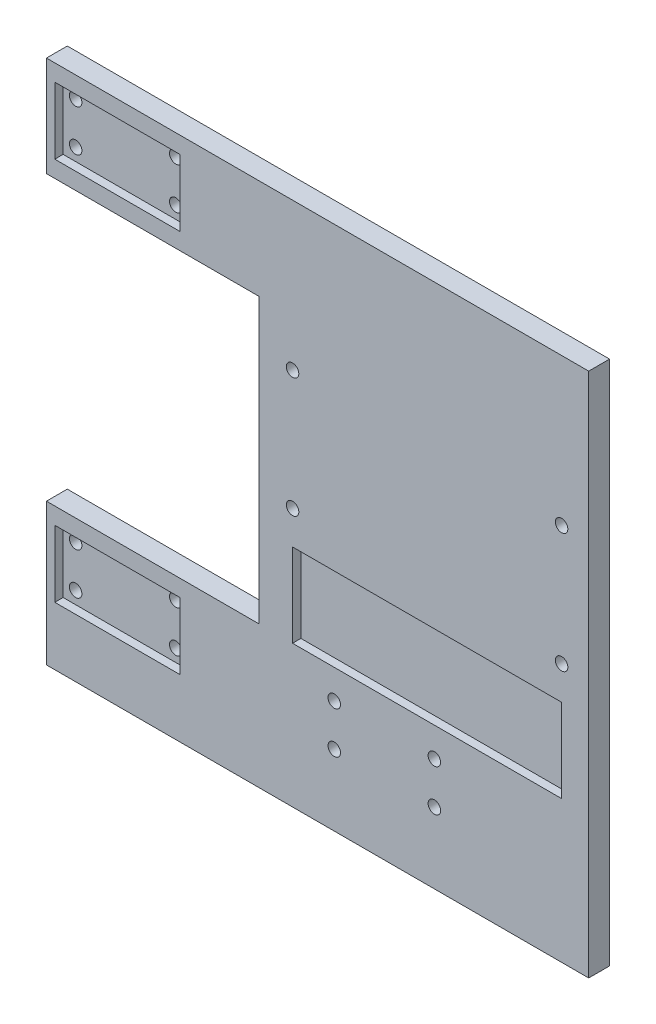
SolidWorks part; units mm, degrees
ref_plane "前视基准面" through (0, 0, 0) normal (0, 0, 1) x (1, 0, 0)
ref_plane "上视基准面" through (0, 0, 0) normal (0, 1, 0) x (1, 0, 0)
ref_plane "右视基准面" through (0, 0, 0) normal (1, 0, 0) x (0, 0, -1)
other "Configuration Table"
sketch "草图1" plane through (0, 0, 0) normal (0, 0, 1) x (1, 0, 0)
  line L0 (0, 0) -> (0, 30)
  line L1 (0, 30) -> (120, 30)
  line L2 (120, 30) -> (120, -96)
  line L3 (120, -96) -> (0, -96)
  line L4 (0, -96) -> (0, -56)
  line L5 (0, -56) -> (45, -56)
  line L6 (45, -56) -> (45, 0)
  line L7 (45, 0) -> (0, 0)
  dimension "D1" = 30
  dimension "D2" = 56
  dimension "D3" = 40
  dimension "D4" = 45
  dimension "D5" = 120
  dimension "D6" = 120
extrude "凸台-拉伸2" add sketch "草图1" along normal blind 5
sketch "草图3" plane through (0, 0, 5) normal (0, 0, 1) x (1, 0, 0)
  line L0 (0, 0) -> (0, 10)
  line L1 (0, 30) -> (0, 0) construction
  line L2 (0, 10) -> (17, 10)
  line L3 (-955, -28) -> (49045, -28) construction
  line L4 (2, 1.95) -> (32, 1.95)
  line L5 (2, 1.95) -> (2, 18.05)
  line L6 (2, 18.05) -> (32, 18.05)
  line L7 (32, 1.95) -> (32, 18.05)
  line L8 (2, 1.95) -> (32, 18.05) construction
  line L9 (2, 18.05) -> (32, 1.95) construction
  line L10 (45, 0) -> (45, -56) construction
  line L11 (2, -74.05) -> (32, -57.95) construction
  line L12 (2, -57.95) -> (32, -74.05) construction
  line L13 (32, -57.95) -> (32, -74.05)
  line L14 (2, -74.05) -> (32, -74.05)
  line L15 (2, -57.95) -> (2, -74.05)
  line L16 (2, -57.95) -> (32, -57.95)
  line L17 (0, -66) -> (17, -66)
  line L18 (0, -56) -> (0, -66)
  point P15 (45, -28)
  dimension "D1" = 10
  dimension "D2" = 17
  dimension "D3" = 16.1
  dimension "D4" = 30
extrude "切除-拉伸1" cut sketch "草图3" against normal blind 2
sketch "草图4" plane through (0, 0, 3) normal (0, 0, 1) x (1, 0, 0)
  line L0 (2, 18.05) -> (17, 18.05)
  line L5 (2, 18.05) -> (32, 18.05) construction
  line L6 (17, 18.05) -> (17, 10)
  line L7 (-998, 10) -> (49002, 10) construction
  line L8 (2, 2) -> (32, 2)
  line L9 (2, 2) -> (2, 18)
  line L10 (2, 18) -> (32, 18)
  line L11 (32, 2) -> (32, 18)
  line L12 (2, 2) -> (32, 18) construction
  line L13 (2, 18) -> (32, 2) construction
  line L14 (2, 18) -> (5, 18)
  line L15 (2, 18) -> (2, 15)
  line L16 (2, 15) -> (5, 15)
  line L17 (5, 18) -> (5, 15)
  line L18 (-955, -28) -> (49045, -28) construction
  line L19 (45, 0) -> (45, -56) construction
  circle A0 centre (5, 15) radius 1.55
  circle A1 centre (29, 15) radius 1.55
  circle A2 centre (29, 5) radius 1.55
  circle A3 centre (5, 5) radius 1.55
  circle A4 centre (5, -61) radius 1.55
  circle A5 centre (29, -61) radius 1.55
  circle A6 centre (29, -71) radius 1.55
  circle A7 centre (5, -71) radius 1.55
  point P20 (2, 10)
  point P29 (45, -28)
  dimension "D5" = 3.1
  dimension "D1" = 30
  dimension "D2" = 16
  dimension "D3" = 3
  dimension "D4" = 3
extrude "切除-拉伸2" cut sketch "草图4" against normal up to next contours A1 | A2 | L16 A0 L17 | L17 A0 L16 | A3 | A4 | A7 | A5 | A6
sketch "草图5" plane through (0, 0, 5) normal (0, 0, 1) x (1, 0, 0)
  line L0 (17, -74.05) -> (17, 18.05) construction
  line L1 (2, -74.05) -> (32, -74.05) construction
  line L2 (2, 18.05) -> (32, 18.05) construction
  line L3 (17, -74.05) -> (17, -85.05) construction
  line L4 (17, -85.05) -> (17, -96) construction
  line L5 (0, -96) -> (120, -96) construction
  line L6 (17, -96) -> (77, -96)
  line L7 (45, -56) -> (0, -56) construction
  line L8 (17, -56) -> (49, -56)
  line L9 (17, -56) -> (17, 0)
  line L10 (17, 0) -> (49, 0)
  line L11 (49, -56) -> (49, 0)
  dimension "D1" = 11
  dimension "D2" = 60
  dimension "D3" = 32
extrude "切除-拉伸3" cut sketch "草图5" against normal up to next contours L8 L11 L10 L9
sketch "草图7" plane through (0, 0, 5) normal (0, 0, 1) x (1, 0, 0)
  line L0 (49, -56) -> (59, -56)
  line L2 (59, -56) -> (99.5, -56)
  line L3 (59, -56) -> (59, -15.5)
  line L4 (59, -15.5) -> (99.5, -15.5)
  line L5 (99.5, -56) -> (99.5, -15.5)
  dimension "D1" = 10
  dimension "D2" = 40.5
  dimension "D3" = 40.5
extrude "凸台-拉伸4" add sketch "草图7" along normal blind 2 contours L2 L5 L4 L3
sketch "草图8" plane through (0, 0, 5) normal (0, 0, 1) x (1, 0, 0)
  line L0 (17, -998.05) -> (17, 49001.95) construction
  line L1 (2, 1.95) -> (32, 1.95) construction
  line L2 (59, -56) -> (69.5, -56)
  line L3 (59, -56) -> (99.5, -56) construction
  line L4 (69.5, -1056) -> (69.5, 48944) construction
  line L5 (69.5, -56) -> (69.5, -60.5)
  line L6 (69.5, -60.5) -> (69.5, -70.5)
  line L8 (54.25, -78.75) -> (84.75, -78.75)
  line L9 (54.25, -78.75) -> (54.25, -62.25)
  line L10 (54.25, -62.25) -> (84.75, -62.25)
  line L11 (84.75, -78.75) -> (84.75, -62.25)
  line L12 (54.25, -78.75) -> (84.75, -62.25) construction
  line L13 (54.25, -62.25) -> (84.75, -78.75) construction
  point P5 (17, 1.95)
  dimension "D1" = 10.5
  dimension "D2" = 4.5
  dimension "D3" = 10
  dimension "D4" = 30.5
  dimension "D5" = 16.5
extrude "切除-拉伸4" cut sketch "草图8" against normal blind 2
sketch "草图9" plane through (0, 0, 3) normal (0, 0, 1) x (1, 0, 0)
  line L0 (-945.75, -70.5) -> (49054.25, -70.5) construction
  line L1 (54.25, -62.25) -> (57.5, -62.25)
  line L2 (54.25, -62.25) -> (54.25, -65.5)
  line L3 (54.25, -65.5) -> (57.5, -65.5)
  line L4 (57.5, -62.25) -> (57.5, -65.5)
  line L5 (54.25, -78.75) -> (54.25, -62.25) construction
  line L6 (69.5, -1062.25) -> (69.5, 48937.75) construction
  line L7 (54.25, -62.25) -> (84.75, -62.25) construction
  circle A0 centre (57.5, -65.5) radius 1.55
  circle A1 centre (81.5, -65.5) radius 1.55
  circle A2 centre (81.5, -75.5) radius 1.55
  circle A3 centre (57.5, -75.5) radius 1.55
  point P11 (54.25, -70.5)
  point P16 (69.5, -62.25)
  dimension "D3" = 3.1
  dimension "D1" = 3.25
  dimension "D2" = 3.25
extrude "切除-拉伸6" cut sketch "草图9" against normal through all contours A1 | A0 | A3 | A2
sketch "草图10" plane through (0, 0, 7) normal (0, 0, 1) x (1, 0, 0)
  line L1 (59, -56) -> (119, -56)
  line L2 (59, -56) -> (59, -11)
  line L3 (59, -11) -> (119, -11)
  line L4 (119, -56) -> (119, -11)
  dimension "D1" = 60
  dimension "D2" = 45
extrude "凸台-拉伸5" add sketch "草图10" against normal blind 2
sketch "草图11" plane through (0, 0, 5) normal (0, 0, 1) x (1, 0, 0)
  line L1 (59, -11) -> (119, -11)
  line L2 (59, -11) -> (59, -56)
  line L3 (59, -56) -> (119, -56)
  line L4 (119, -11) -> (119, -56)
extrude "切除-拉伸8" cut sketch "草图11" along normal blind 2
sketch "草图12" plane through (0, 0, 5) normal (0, 0, 1) x (1, 0, 0)
  line L1 (2, 1.95) -> (32, 1.95)
  line L2 (2, 1.95) -> (2, 18.05)
  line L3 (2, 18.05) -> (32, 18.05)
  line L4 (32, 1.95) -> (32, 18.05)
  line L5 (2, -57.95) -> (32, -57.95)
  line L6 (2, -57.95) -> (2, -74.05)
  line L7 (2, -74.05) -> (32, -74.05)
  line L8 (32, -57.95) -> (32, -74.05)
  line L9 (54.25, -62.25) -> (84.75, -62.25)
  line L10 (54.25, -62.25) -> (54.25, -78.75)
  line L11 (54.25, -78.75) -> (84.75, -78.75)
  line L12 (84.75, -62.25) -> (84.75, -78.75)
extrude "凸台-拉伸6" add sketch "草图12" against normal blind 5
sketch "草图13" plane through (0, 0, 5) normal (0, 0, 1) x (1, 0, 0)
  line L0 (0, 0) -> (0, 10)
  line L1 (0, 30) -> (0, 0) construction
  line L2 (0, 10) -> (2, 10)
  line L3 (-951, -28) -> (49049, -28) construction
  line L4 (2, 10) -> (32, 10)
  line L5 (2, 10) -> (2, 26)
  line L6 (2, 26) -> (32, 26)
  line L7 (32, 10) -> (32, 26)
  line L8 (49, -56) -> (49, 0) construction
  line L9 (32, -66) -> (32, -82)
  line L10 (2, -82) -> (32, -82)
  line L11 (2, -66) -> (2, -82)
  line L12 (2, -66) -> (32, -66)
  line L13 (-998, 18) -> (49002, 18) construction
  line L14 (2, 26) -> (5, 26)
  line L15 (2, 26) -> (2, 23)
  line L16 (2, 23) -> (5, 23)
  line L17 (5, 26) -> (5, 23)
  line L19 (17, -974) -> (17, 49026) construction
  circle A0 centre (5, 23) radius 1.5
  circle A1 centre (29, 23) radius 1.5
  circle A2 centre (29, 13) radius 1.5
  circle A3 centre (5, 13) radius 1.5
  circle A4 centre (5, -69) radius 1.5
  circle A5 centre (29, -69) radius 1.5
  circle A6 centre (29, -79) radius 1.5
  circle A7 centre (5, -79) radius 1.5
  point P14 (49, -28)
  point P25 (2, 18)
  point P30 (17, 26)
  dimension "D7" = 3
  dimension "D1" = 10
  dimension "D2" = 2
  dimension "D3" = 16
  dimension "D4" = 30
  dimension "D5" = 3
  dimension "D6" = 3
extrude "切除-拉伸10" cut sketch "草图13" against normal blind 5 contours A4 | A7 | A2 | A1 | A3 | A6 | A5 | A0
sketch "草图14" plane through (0, 0, 5) normal (0, 0, 1) x (1, 0, 0)
  line L1 (2, 26) -> (32, 26)
  line L2 (2, 26) -> (2, 10)
  line L3 (2, 10) -> (32, 10)
  line L4 (32, 26) -> (32, 10)
  line L5 (2, -66) -> (32, -66)
  line L6 (2, -66) -> (2, -82)
  line L7 (2, -82) -> (32, -82)
  line L8 (32, -66) -> (32, -82)
extrude "切除-拉伸11" cut sketch "草图14" against normal blind 2
sketch "草图15" plane through (0, 0, 5) normal (0, 0, 1) x (1, 0, 0)
  line L0 (-2, 2) -> (-2, -58)
  line L1 (0, 0) -> (49, 0)
  line L2 (0, 0) -> (0, -56)
  line L3 (0, -56) -> (49, -56)
  line L4 (49, 0) -> (49, -56)
  line L5 (-2, -58) -> (51, -58)
  line L6 (51, 2) -> (51, -58)
  line L7 (-2, 2) -> (51, 2)
  dimension "D1" = 2
extrude "切除-拉伸12" cut sketch "草图15" against normal blind 5
sketch "草图16" plane through (0, 0, 5) normal (0, 0, 1) x (1, 0, 0)
  line L0 (51, -58) -> (61, -58)
  line L1 (61, -58) -> (61, -66)
  line L3 (61, -66) -> (91, -66)
  line L4 (61, -66) -> (61, -82)
  line L5 (61, -82) -> (91, -82)
  line L6 (91, -66) -> (91, -82)
  dimension "D1" = 10
  dimension "D2" = 30
  dimension "D3" = 16
extrude "切除-拉伸13" cut sketch "草图16" against normal blind 2 contours L6 L3 L4 L5
sketch "草图17" plane through (0, 0, 3) normal (0, 0, 1) x (1, 0, 0)
  line L0 (-939, -74) -> (49061, -74) construction
  line L1 (61, -66) -> (64, -66)
  line L2 (61, -66) -> (61, -69)
  line L3 (61, -69) -> (64, -69)
  line L4 (64, -66) -> (64, -69)
  line L5 (61, -66) -> (61, -82) construction
  line L6 (76, -1066) -> (76, 48934) construction
  line L7 (61, -66) -> (91, -66) construction
  circle A0 centre (64, -69) radius 1.5
  circle A1 centre (88, -69) radius 1.5
  circle A2 centre (88, -79) radius 1.5
  circle A3 centre (64, -79) radius 1.5
  point P11 (61, -74)
  point P16 (76, -66)
  dimension "D3" = 3
  dimension "D1" = 3
  dimension "D2" = 3
extrude "切除-拉伸15" cut sketch "草图17" against normal through all contours A1 | A2 | A3 | A0
sketch "草图18" plane through (0, 0, 5) normal (0, 0, 1) x (1, 0, 0)
  line L0 (76, -66) -> (76, -46)
  line L1 (61, -66) -> (91, -66) construction
  line L2 (76, -46) -> (106, -46)
  line L3 (76, -46) -> (66, -46)
  line L4 (66, -46) -> (50, -46)
  line L5 (66, -46) -> (106, -46)
  line L6 (66, -46) -> (66, -6)
  line L7 (66, -6) -> (106, -6)
  line L8 (106, -46) -> (106, -6)
  line L9 (106, -46) -> (122, -46)
  line L11 (120, 30) -> (130, 30)
  line L12 (120, 30) -> (120, -96)
  line L13 (120, -96) -> (130, -96)
  line L14 (130, 30) -> (130, -96)
  dimension "D1" = 20
  dimension "D2" = 30
  dimension "D3" = 10
  dimension "D4" = 40
  dimension "D5" = 16
  dimension "D6" = 16
  dimension "D7" = 10
extrude "凸台-拉伸7" add sketch "草图18" against normal blind 5
sketch "草图19" plane through (0, 0, 5) normal (0, 0, 1) x (1, 0, 0)
  line L1 (61, -66) -> (91, -66)
  line L2 (61, -66) -> (61, -82)
  line L3 (61, -82) -> (91, -82)
  line L4 (91, -66) -> (91, -82)
extrude "凸台-拉伸8" add sketch "草图19" against normal blind 5
sketch "草图20" plane through (0, 0, 5) normal (0, 0, 1) x (1, 0, 0)
  line L0 (32, -74) -> (72, -74)
  line L1 (32, -66) -> (32, -82) construction
  line L2 (51, -58) -> (71, -58)
  line L3 (71, -58) -> (71, -38)
  line L4 (71, -38) -> (81, -38)
  line L5 (71, -38) -> (111, -38)
  line L6 (71, -38) -> (71, 2)
  line L7 (71, 2) -> (111, 2)
  line L8 (111, -38) -> (111, 2)
  line L9 (81, -38) -> (81, -74)
  line L10 (71, -38) -> (55, -38)
  line L11 (111, -38) -> (127, -38)
  line L13 (55, -38) -> (127, -38)
  line L14 (55, -38) -> (55, -1.3)
  line L15 (55, -1.3) -> (127, -1.3)
  line L16 (127, -38) -> (127, -1.3)
  line L17 (66, -82) -> (96, -82)
  line L18 (66, -82) -> (66, -66)
  line L19 (66, -66) -> (96, -66)
  line L20 (96, -82) -> (96, -66)
  line L21 (66, -82) -> (96, -66) construction
  line L22 (66, -66) -> (96, -82) construction
  dimension "D1" = 40
  dimension "D2" = 20
  dimension "D3" = 20
  dimension "D4" = 40
  dimension "D5" = 40
  dimension "D6" = 10
  dimension "D7" = 16
  dimension "D8" = 16
  dimension "D9" = 36.7
  dimension "D10" = 16
  dimension "D11" = 30
extrude "切除-拉伸17" cut sketch "草图20" against normal blind 2
sketch "草图21" plane through (0, 0, 3) normal (0, 0, 1) x (1, 0, 0)
  line L0 (-945, -19.65) -> (49055, -19.65) construction
  line L1 (55, -1.3) -> (59, -1.3)
  line L2 (55, -1.3) -> (55, -5.3)
  line L3 (55, -5.3) -> (59, -5.3)
  line L4 (59, -1.3) -> (59, -5.3)
  line L5 (55, -38) -> (55, -1.3) construction
  line L6 (91, -1001.3) -> (91, 48998.7) construction
  line L7 (55, -1.3) -> (127, -1.3) construction
  line L8 (-934, -74) -> (49066, -74) construction
  line L9 (66, -66) -> (69, -66)
  line L10 (66, -66) -> (66, -69)
  line L11 (66, -69) -> (69, -69)
  line L12 (69, -66) -> (69, -69)
  line L13 (66, -82) -> (66, -66) construction
  line L14 (81, -1066) -> (81, 48934) construction
  line L15 (66, -66) -> (96, -66) construction
  circle A0 centre (59, -5.3) radius 1.5
  circle A1 centre (123, -5.3) radius 1.5
  circle A2 centre (123, -34) radius 1.5
  circle A3 centre (59, -34) radius 1.5
  circle A4 centre (69, -69) radius 1.5
  circle A5 centre (93, -69) radius 1.5
  circle A6 centre (93, -79) radius 1.5
  circle A7 centre (69, -79) radius 1.5
  point P11 (55, -19.65)
  point P16 (91, -1.3)
  point P33 (66, -74)
  point P38 (81, -66)
  dimension "D3" = 3
  dimension "D6" = 3
  dimension "D1" = 4
  dimension "D2" = 4
  dimension "D4" = 3
  dimension "D5" = 3
extrude "切除-拉伸18" cut sketch "草图21" against normal through all contours L3 A0 L4 | L4 A0 L3 | A3 | A2 | A1 | A5 | A7 | A6 | A4
sketch "草图22" plane through (0, 0, 3) normal (0, 0, 1) x (1, 0, 0)
  circle A0 centre (123, -5.3) radius 1.5
  circle A1 centre (123, -34) radius 1.5
extrude "凸台-拉伸10" add sketch "草图22" against normal blind 3
sketch "草图23" plane through (0, 0, 3) normal (0, 0, 1) x (1, 0, 0)
  line L1 (127, -1.3) -> (123.5, -1.3)
  line L2 (127, -1.3) -> (127, -5.3)
  line L3 (127, -5.3) -> (123.5, -5.3)
  line L4 (123.5, -1.3) -> (123.5, -5.3)
  line L5 (127, -38) -> (123.5, -38)
  line L6 (127, -38) -> (127, -34)
  line L7 (127, -34) -> (123.5, -34)
  line L8 (123.5, -38) -> (123.5, -34)
  circle A0 centre (123.5, -5.3) radius 1.5
  circle A1 centre (123.5, -34) radius 1.5
  dimension "D3" = 3
  dimension "D6" = 3
  dimension "D1" = 3.5
  dimension "D2" = 4
  dimension "D4" = 3.5
  dimension "D5" = 4
extrude "切除-拉伸19" cut sketch "草图23" against normal through all contours L4 A0 L3 | L3 A0 L4 | A1
sketch "草图24" plane through (0, 0, 5) normal (0, 0, 1) x (1, 0, 0)
  line L1 (55, -1.3) -> (127, -1.3)
  line L2 (55, -1.3) -> (55, -38)
  line L3 (55, -38) -> (127, -38)
  line L4 (127, -1.3) -> (127, -38)
  circle A0 centre (59, -5.3) radius 1.5
  circle A1 centre (123.5, -5.3) radius 1.5
  circle A2 centre (123.5, -34) radius 1.5
  circle A3 centre (59, -34) radius 1.5
extrude "凸台-拉伸11" add sketch "草图24" against normal blind 5
sketch "草图25" plane through (0, 0, 3) normal (0, 0, 1) x (1, 0, 0)
  line L1 (66, -66) -> (96, -66)
  line L2 (66, -66) -> (66, -82)
  line L3 (66, -82) -> (96, -82)
  line L4 (96, -66) -> (96, -82)
sketch "草图26" plane through (0, 0, 5) normal (0, 0, 1) x (1, 0, 0)
  line L1 (66, -66) -> (96, -66)
  line L2 (66, -66) -> (66, -82)
  line L3 (66, -82) -> (96, -82)
  line L4 (96, -66) -> (96, -82)
  circle A0 centre (69, -69) radius 1.5
  circle A1 centre (69, -79) radius 1.5
  circle A2 centre (93, -79) radius 1.5
  circle A3 centre (93, -69) radius 1.5
extrude "凸台-拉伸12" add sketch "草图26" against normal blind 5
sketch "草图27" plane through (0, 0, 5) normal (0, 0, 1) x (1, 0, 0)
  line L0 (51, 2) -> (51, 6)
  line L1 (-949, -28) -> (49051, -28) construction
  line L2 (51, 6) -> (0, 6)
  line L3 (51, 6) -> (51, 2)
  line L4 (51, 2) -> (0, 2)
  line L5 (0, 6) -> (0, 2)
  line L6 (51, -58) -> (51, 2) construction
  line L8 (0, -62) -> (0, -58)
  line L9 (51, -58) -> (0, -58)
  line L10 (51, -62) -> (51, -58)
  line L11 (51, -62) -> (0, -62)
  line L12 (51, -58) -> (51, -62)
  point P11 (51, -28)
  line M10 (0, 30) -> (0, 2)
  line M11 (0, 2) -> (51, 2)
  line M13 (51, -58) -> (0, -58)
  line M14 (0, -58) -> (0, -96)
  dimension "D1" = 4
extrude "切除-拉伸22" cut sketch "草图27" against normal blind 5 contours L0 L2 M10 M11 | L11 L10 M13 M14
sketch "草图29" plane through (0, 0, 5) normal (0, 0, 1) x (1, 0, 0)
  line L0 (130, 30) -> (130, -96) construction
  line L1 (51, -62) -> (130, -62)
  line L2 (51, -62) -> (51, -42)
  line L3 (51, -42) -> (130, -42)
  line L4 (130, -62) -> (130, -42)
  line L5 (59, -34) -> (59, -62)
  line L6 (123.5, -34) -> (123.5, -62)
  dimension "D1" = 20
extrude "切除-拉伸24" cut sketch "草图29" against normal blind 2 contours L6 L3 L5 L1
